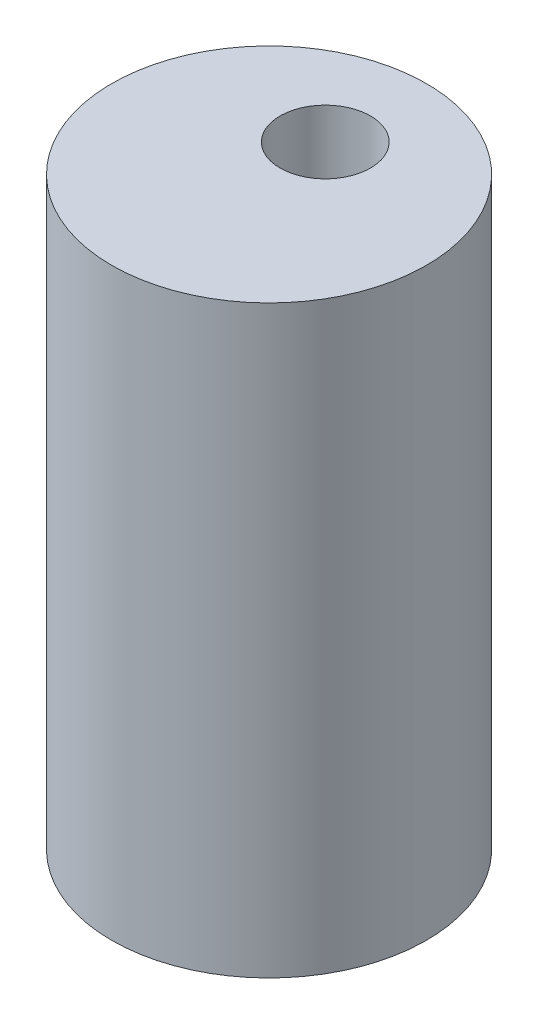
SolidWorks part; units mm, degrees
material "6061 Alloy"
ref_plane "Front" through (0, 0, 0) normal (0, 0, 1) x (1, 0, 0)
ref_plane "Top" through (0, 0, 0) normal (0, 1, 0) x (1, 0, 0)
ref_plane "Right" through (0, 0, 0) normal (1, 0, 0) x (0, 0, -1)
sketch "Sketch1" plane through (0, 0, 0) normal (0, 1, 0) x (1, 0, 0)
  circle A0 centre (0, 0) radius 8.89
  dimension "D1" = 17.78
extrude "Boss-Extrude1" add sketch "Sketch1" along normal blind 33.02
hole_wizard "1/4-20 Tapped Hole1" positions "Sketch3" profile "Sketch4" tap size "1/4-20" standard "ANSI Inch"
sketch "Sketch3" plane through (0, 33.02, 0) normal (0, 1, 0) x (1, 0, 0)
  point P0 (0, 3.175)
  dimension "D1" = 3.175
sketch "Sketch4" plane through (0, 33.02, -3.175) normal (1, 0, 0) x (0, 0, 1)
  line L0 (0, 0) -> (0, 14.2338)
  line L1 (0, 14.2338) -> (2.5527, 12.7)
  line L2 (2.5527, 12.7) -> (2.5527, 0)
  line L5 (2.5527, 0) -> (0, 0)
  line L10 (0, 14.2338) -> (-2.5527, 12.7) construction
  line L11 (0, -6.35) -> (0, 107.95) construction
  dimension "Tap Drill Dia." = 5.1054
  dimension "Tap Drill Depth" = 12.7
  dimension "Drill Angle" = 118
cosmetic thread "Hole Thread1"
hole_wizard "Ø6.0mm Dowel Hole1" positions "Sketch6" profile "Sketch7" hole size "Ø6.0" standard "ANSI Metric"
sketch "Sketch6" plane through (0, 0, 0) normal (0, -1, 0) x (-1, 0, 0)
  point P0 (0, 0)
sketch "Sketch7" plane through (0, 0, 0) normal (1, 0, 0) x (0, 0, -1)
  line L0 (0, 0) -> (0, 19.8026)
  line L1 (0, 19.8026) -> (3, 18)
  line L2 (3, 18) -> (3, 0)
  line L5 (3, 0) -> (0, 0)
  line L10 (0, 19.8026) -> (-3, 18) construction
  line L11 (0, -6.35) -> (0, 107.95) construction
  dimension "Hole Dia." = 6
  dimension "Hole Depth" = 18
  dimension "Drill Angle" = 118
ref_plane "Plane1" through (0, 0, -8.89) normal (0, 0, -1) x (-1, 0, 0)
hole_wizard "M4x0.7 Tapped Hole1" positions "Sketch8" profile "Sketch9" tap size "M4x0.7" standard "ANSI Metric"
sketch "Sketch8" plane through (0, 0, -8.89) normal (0, 0, -1) x (-1, 0, 0)
  line L0 (0, 10) -> (0, 0) construction
  point P0 (0, 10)
  dimension "D1" = 10
sketch "Sketch9" plane through (0, 10, -8.89) normal (1, 0, 0) x (0, 1, 0)
  line L0 (0, 0) -> (0, 5.89)
  line L1 (0, 5.89) -> (1.65, 5.89)
  line L2 (1.65, 5.89) -> (1.65, 0)
  line L5 (1.65, 0) -> (0, 0)
  line L11 (0, -6.35) -> (0, 107.95) construction
  dimension "Thru Tap Drill Dia." = 3.3
  dimension "Thru Tap Drill Depth" = 5.89
cosmetic thread "Hole Thread2"
